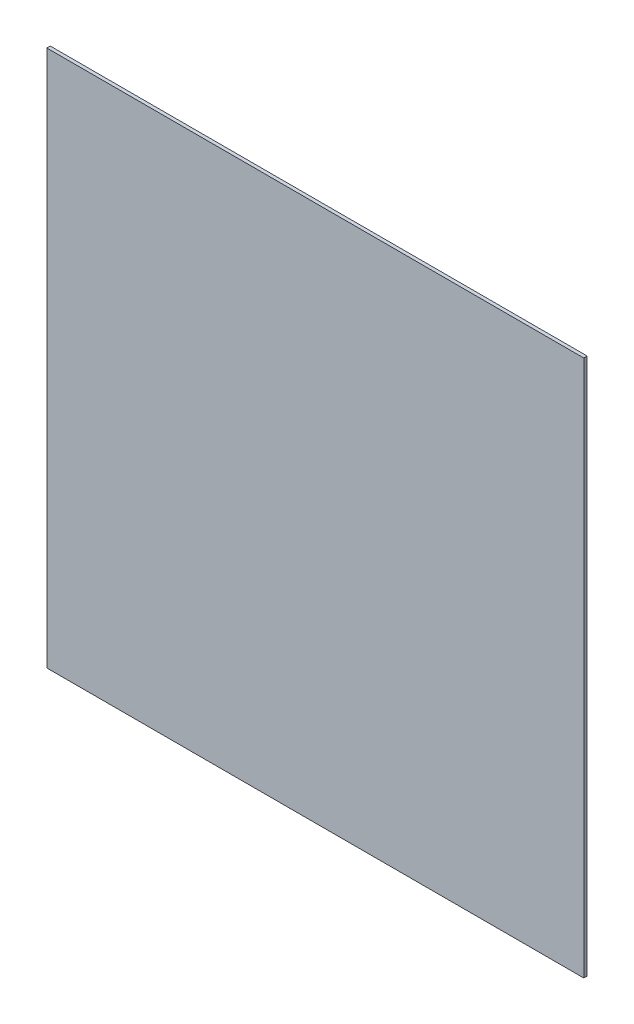
SolidWorks part; units mm, degrees
ref_plane "Front Plane" through (0, 0, 0) normal (0, 0, 1) x (1, 0, 0)
ref_plane "Top Plane" through (0, 0, 0) normal (0, 1, 0) x (1, 0, 0)
ref_plane "Right Plane" through (0, 0, 0) normal (1, 0, 0) x (0, 0, -1)
sketch "Sketch1" plane through (0, 0, 0) normal (0, 0, 1) x (1, 0, 0)
  line L1 (1597.2049, -84.2434) -> (1127.3049, -84.2434)
  line L2 (1597.2049, -84.2434) -> (1597.2049, -554.1434)
  line L3 (1597.2049, -554.1434) -> (1127.3049, -554.1434)
  line L4 (1127.3049, -84.2434) -> (1127.3049, -554.1434)
  dimension "D1" = 469.9
  dimension "D2" = 469.9
extrude "Boss-Extrude1" add sketch "Sketch1" along normal blind 3
